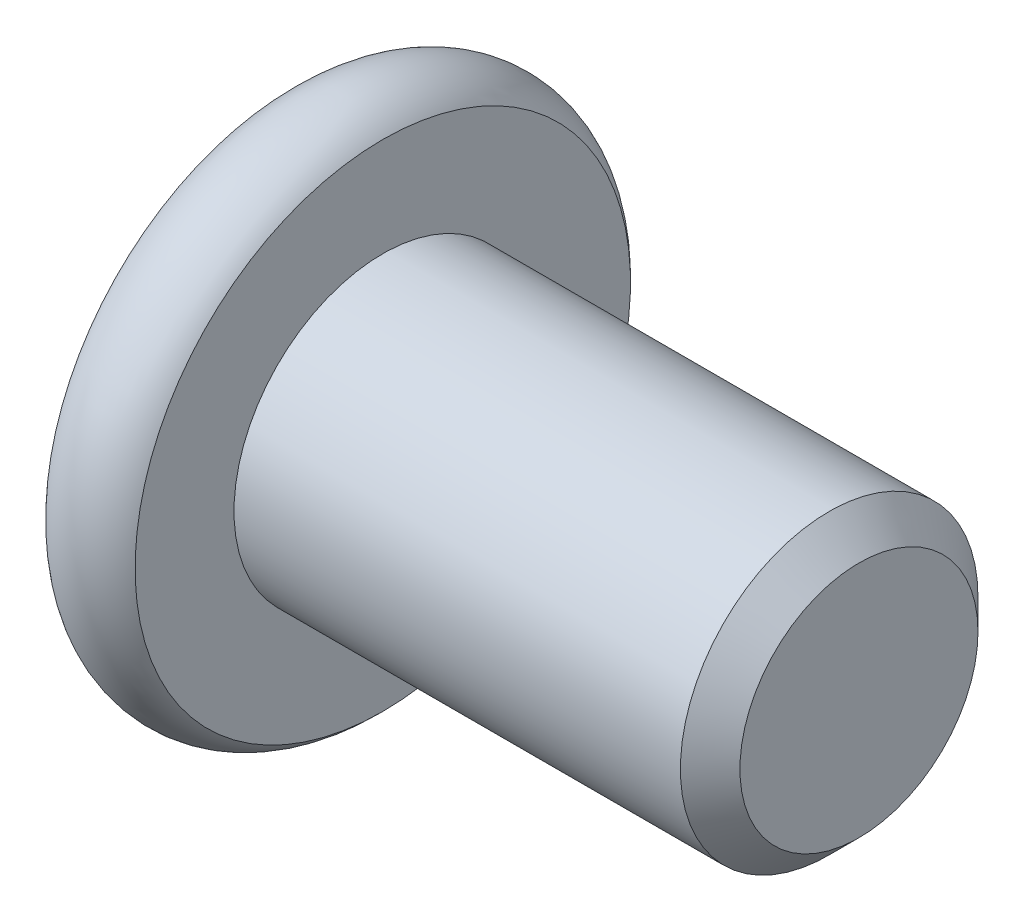
SolidWorks part; units mm, degrees
material "Alloy Steel"
ref_plane "Front Plane" through (0, 0, 0) normal (0, 0, 1) x (1, 0, 0)
ref_plane "Top Plane" through (0, 0, 0) normal (0, 1, 0) x (1, 0, 0)
ref_plane "Right Plane" through (0, 0, 0) normal (1, 0, 0) x (0, 0, -1)
other "M5 x 15"
sketch "Sketch2" plane through (0, 0, 0) normal (1, 0, 0) x (0, 0, -1)
  circle A0 centre (0, 0) radius 2.5
  dimension "D1" = 5
extrude "Boss-Extrude1" add sketch "Sketch2" against normal blind 8
chamfer "Chamfer1" distance 0.5 angle 45 1 edges at (0, 0, -2.5)
sketch "Sketch6" plane through (0, 0, 0) normal (0, 0, 1) x (1, 0, 0)
  line L0 (-9.5, 0) -> (-9.5, 4.1614)
  line L1 (-9.5, 0) -> (-8, 0)
  line L2 (-8.75, 0) -> (-8.75, 3.5) construction
  line L6 (-8, 4.1614) -> (-8, 0)
  line L8 (-8, 0) -> (-14.6471, 0) construction
  line L10 (-8, 2.5) -> (-8, -2.5) construction
  arc A0 (-9.5, 4.1614) -> (-8, 4.1614) centre (-8.75, 3.5) cw
  dimension "D3" = 1
  dimension "D1" = 1.5
  dimension "D2" = 9
revolve "Revolve1" add sketch "Sketch6" angle 360 about L8
sketch "Sketch7" plane through (-9.5, 0, 0) normal (-1, 0, 0) x (0, 0, 1)
  line L1 (0, 1.7321) -> (-1.5, 0.866)
  line L2 (-1.5, 0.866) -> (-1.5, -0.866)
  line L3 (-1.5, -0.866) -> (0, -1.7321)
  line L4 (0, -1.7321) -> (1.5, -0.866)
  line L5 (1.5, -0.866) -> (1.5, 0.866)
  line L6 (1.5, 0.866) -> (0, 1.7321)
  circle A0 centre (0, 0) radius 1.5 construction
  dimension "D1" = 3
extrude "Cut-Extrude1" cut sketch "Sketch7" against normal blind 2.3
sketch "Sketch8" plane through (-9.5, 0, 0) normal (-1, 0, 0) x (0, 0, 1)
  circle A0 centre (0, 0) radius 1.7821
  dimension "D1" = 0.05
extrude "Cut-Extrude2" cut sketch "Sketch8" against normal blind 1 draft 45
